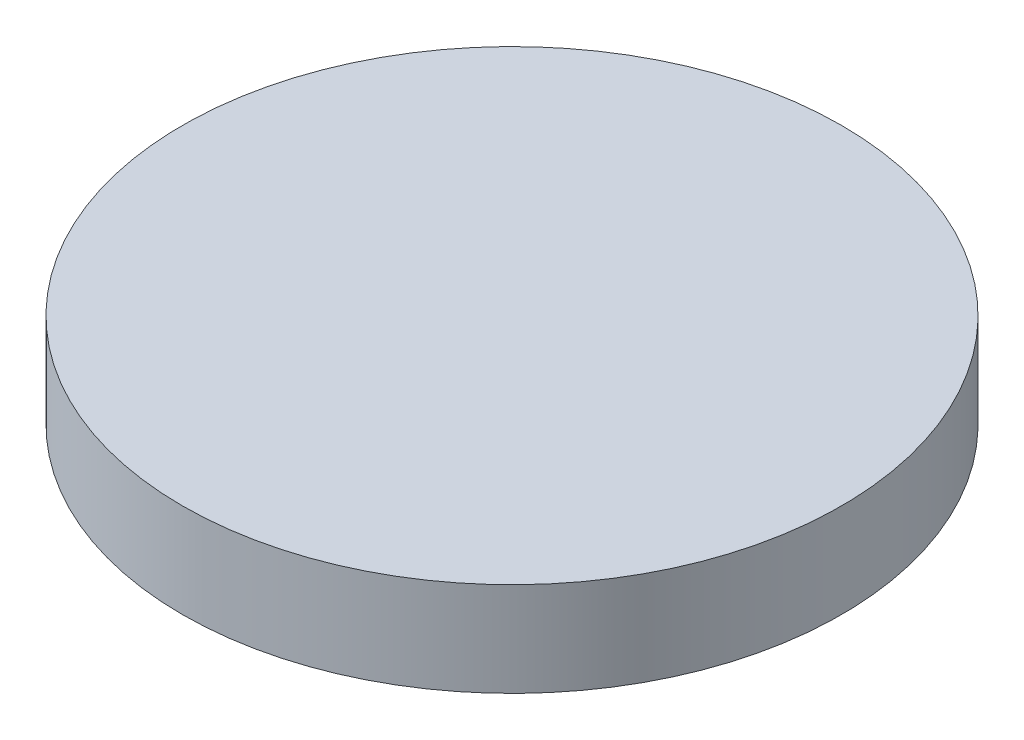
SolidWorks part; units mm, degrees
ref_plane "Front Plane" through (0, 0, 0) normal (0, 0, 1) x (1, 0, 0)
ref_plane "Top Plane" through (0, 0, 0) normal (0, 1, 0) x (1, 0, 0)
ref_plane "Right Plane" through (0, 0, 0) normal (1, 0, 0) x (0, 0, -1)
sketch "Sketch1" plane through (0, 0, 0) normal (0, 1, 0) x (1, 0, 0)
  circle A0 centre (0, 0) radius 7
  dimension "D1" = 14
extrude "Boss-Extrude1" add sketch "Sketch1" along normal blind 2
